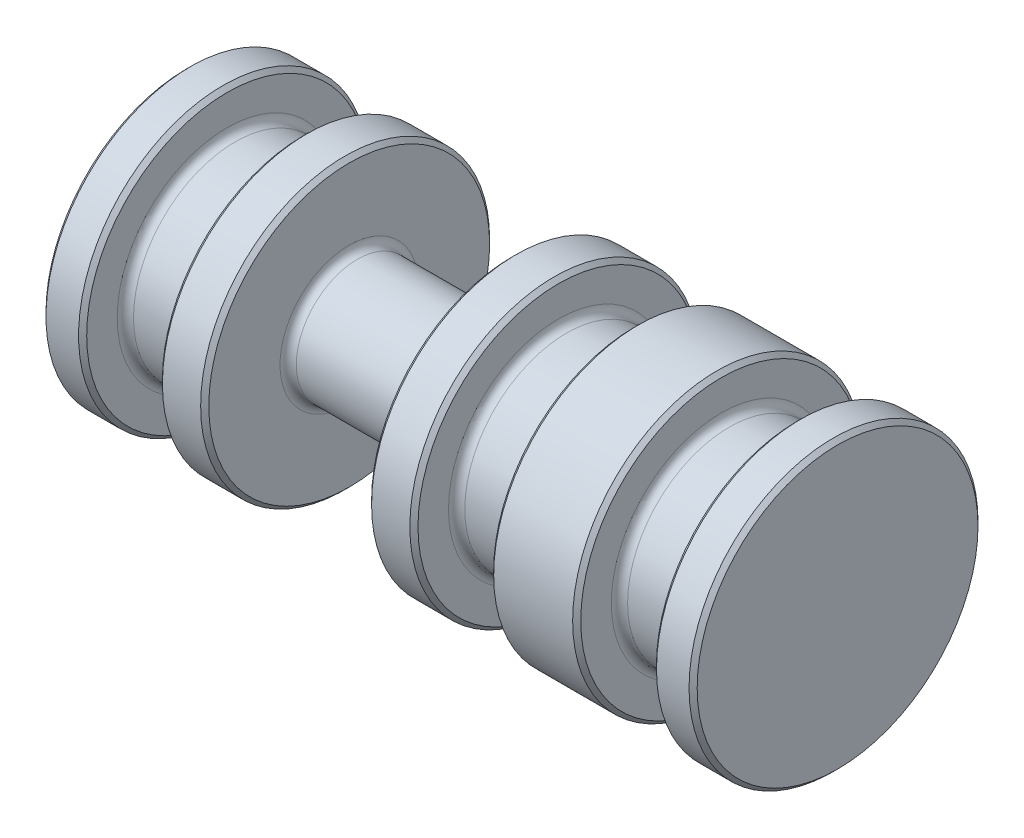
SolidWorks part; units mm, degrees
material "6063-T6"
ref_plane "Front Plane" through (0, 0, 0) normal (0, 0, 1) x (1, 0, 0)
ref_plane "Top Plane" through (0, 0, 0) normal (0, 1, 0) x (1, 0, 0)
ref_plane "Right Plane" through (0, 0, 0) normal (1, 0, 0) x (0, 0, -1)
sketch "Sketch1" plane through (0, 0, 0) normal (1, 0, 0) x (0, 0, -1)
  circle A0 centre (0, 0) radius 4.5085
  dimension "D1" = 9.017
extrude "Boss-Extrude1" add sketch "Sketch1" along normal blind 20.32
sketch "Sketch2" plane through (0, 0, 0) normal (0, 0, 1) x (1, 0, 0)
  line L0 (-1.6174, 0) -> (23.3579, 0) construction
  line L1 (1.27, 4.5085) -> (3.6322, 4.5085)
  line L2 (3.6322, 4.5085) -> (3.6322, 3.175)
  line L3 (3.6322, 3.175) -> (1.27, 3.175)
  line L4 (1.27, 3.175) -> (1.27, 4.5085)
  line L5 (0, 4.5085) -> (0, -4.5085) construction
  line L6 (15.24, 5.6982) -> (15.24, -5.5364) construction
  line L7 (20.32, -4.5085) -> (20.32, 4.5085) construction
  line L8 (16.6878, 4.5085) -> (19.05, 4.5085)
  line L9 (19.05, 4.5085) -> (19.05, 3.175)
  line L10 (19.05, 3.175) -> (16.6878, 3.175)
  line L11 (16.6878, 3.175) -> (16.6878, 4.5085)
  line L12 (11.6078, 4.5085) -> (13.97, 4.5085)
  line L13 (13.97, 4.5085) -> (13.97, 3.175)
  line L14 (13.97, 3.175) -> (11.6078, 3.175)
  line L15 (11.6078, 3.175) -> (11.6078, 4.5085)
  line L17 (5.08, 4.5085) -> (10.16, 4.5085)
  line L18 (5.08, 4.5085) -> (5.08, 1.905)
  line L19 (5.08, 1.905) -> (10.16, 1.905)
  line L20 (10.16, 4.5085) -> (10.16, 1.905)
  point P25 (0, 0)
  dimension "D1" = 9.017
  dimension "D2" = 6.35
  dimension "D3" = 2.3622
  dimension "D4" = 1.27
  dimension "D5" = 5.08
  dimension "D6" = 1.27
  dimension "D7" = 6.35
  dimension "D8" = 5.08
  dimension "D9" = 10.16
  dimension "D10" = 3.81
revolve "Cut-Revolve1" cut sketch "Sketch2" angle 360 about L0
fillet "Fillet1" radius 0.254 8 edges at (19.05, 0, 3.175) (16.6878, 0, 3.175) (13.97, 0, 3.175) (11.6078, 0, 3.175) (10.16, 0, 1.905) (5.08, 0, 1.905) (3.6322, 0, 3.175) (1.27, 0, 3.175)
chamfer "Chamfer1" distance 0.127 angle 45 5 edges at (10.16, 0, 4.5085) (0, 0, -4.5085) (19.05, 0, 4.5085) (13.97, 0, 4.5085) (3.6322, 0, 4.5085)
chamfer "Chamfer2" distance 0.127 angle 45 5 edges at (20.32, 0, -4.5085) (16.6878, 0, 4.5085) (11.6078, 0, 4.5085) (5.08, 0, 4.5085) (1.27, 0, 4.5085)
